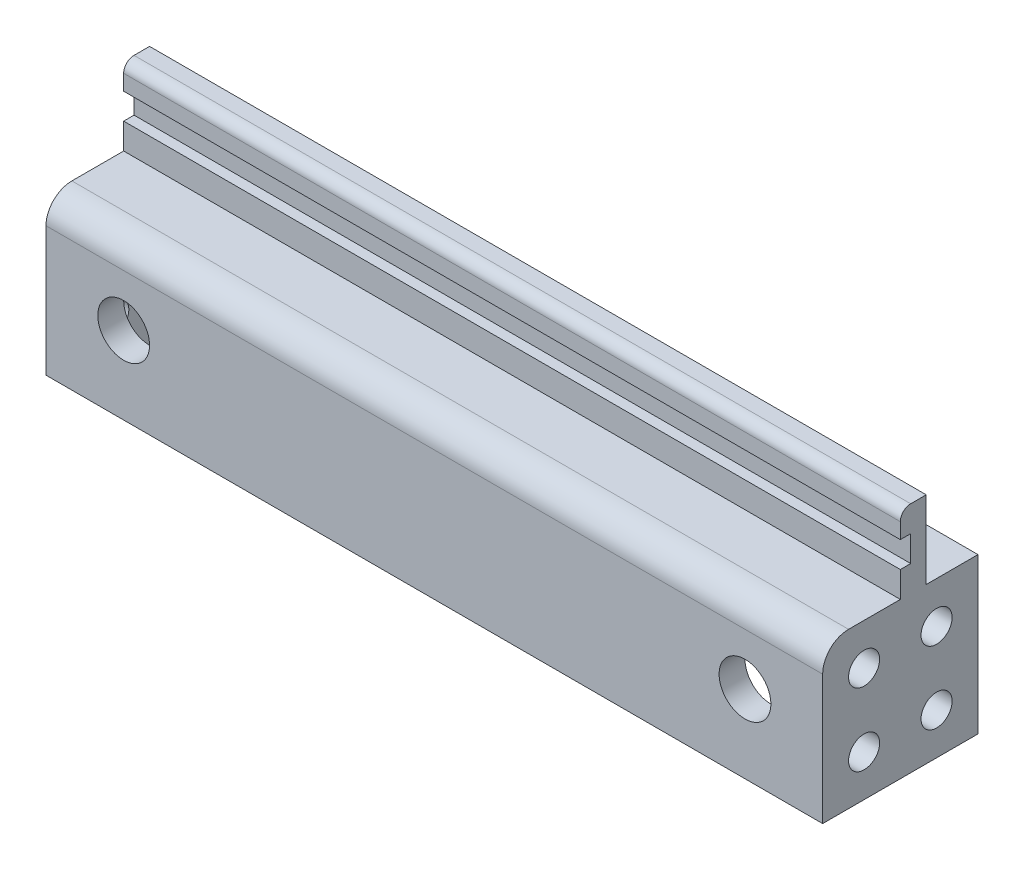
SolidWorks part; units mm, degrees
ref_plane "Front Plane" through (0, 0, 0) normal (0, 0, 1) x (1, 0, 0)
ref_plane "Top Plane" through (0, 0, 0) normal (0, 1, 0) x (1, 0, 0)
ref_plane "Right Plane" through (0, 0, 0) normal (1, 0, 0) x (0, 0, -1)
sketch "Sketch2" plane through (0, 0, 0) normal (0, 1, 0) x (1, 0, 0)
  line L0 (0, 0) -> (-150, 0)
  line L1 (-150, 0) -> (-150, 30)
  line L2 (-150, 30) -> (0, 30)
  line L3 (0, 30) -> (0, 0)
  dimension "D1" = 150
  dimension "D2" = 30
extrude "Boss-Extrude1" add sketch "Sketch2" along normal blind 30
shell "Shell1" thickness 5
sketch "Sketch3" plane through (-150, 0, 0) normal (-1, 0, 0) x (0, 0, 1)
  line L0 (-30, 30) -> (-30, 0) construction
  line L1 (-30, 30) -> (0, 30) construction
  line L2 (0, 30) -> (0, 0) construction
  line L3 (-30, 0) -> (0, 0) construction
  circle A0 centre (-22, 22) radius 3
  circle A1 centre (-8, 22) radius 3
  circle A2 centre (-8, 8) radius 3
  circle A3 centre (-22, 8) radius 3
  dimension "D1" = 6
  dimension "D2" = 8
  dimension "D3" = 8
  dimension "D4" = 8
  dimension "D5" = 8
extrude "Cut-Extrude1" cut sketch "Sketch3" against normal through all both and the other way through all
sketch "Sketch5" plane through (0, 0, 0) normal (0, 0, 1) x (1, 0, 0)
  line L3 (-135, 30) -> (-135, 0) construction
  line L4 (-150, 30) -> (0, 30) construction
  line L5 (-150, 0) -> (0, 0) construction
  line L6 (-150, 30) -> (-150, 0) construction
  line L7 (-15, 30) -> (-15, 0) construction
  line L8 (0, 30) -> (0, 0) construction
  circle A0 centre (-135, 15) radius 5
  circle A2 centre (-15, 15) radius 5
  point P12 (-135, 15)
  dimension "D3" = 10
  dimension "D2" = 15
  dimension "D1" = 15
extrude "Cut-Extrude2" cut sketch "Sketch5" against normal through all both and the other way through all
sketch "Sketch6" plane through (0, 30, 0) normal (0, 1, 0) x (1, 0, 0)
  line L0 (0, 0) -> (0, 30) construction
  line L1 (-150, 20) -> (0, 20)
  line L2 (-150, 20) -> (-150, 15)
  line L3 (-150, 15) -> (0, 15)
  line L4 (0, 20) -> (0, 15)
  line L5 (0, 30) -> (-150, 30) construction
  line L6 (-150, 30) -> (-150, 0) construction
  dimension "D1" = 10
extrude "Boss-Extrude3" add sketch "Sketch6" along normal blind 15
sketch "Sketch7" plane through (0, 0, -15) normal (0, 0, 1) x (1, 0, 0)
  line L0 (-150, 45) -> (-150, 30) construction
  line L1 (-150, 40) -> (0, 40)
  line L2 (-150, 40) -> (-150, 35)
  line L3 (-150, 35) -> (0, 35)
  line L4 (0, 40) -> (0, 35)
  line L5 (0, 45) -> (0, 30) construction
  line L6 (-150, 45) -> (0, 45) construction
  dimension "D1" = 5
  dimension "D2" = 5
extrude "Cut-Extrude3" cut sketch "Sketch7" against normal blind 2
fillet "Fillet1" radius 2 1 edges at (-75, 45, -15)
fillet "Fillet2" radius 5 1 edges at (-75, 30, 0)
